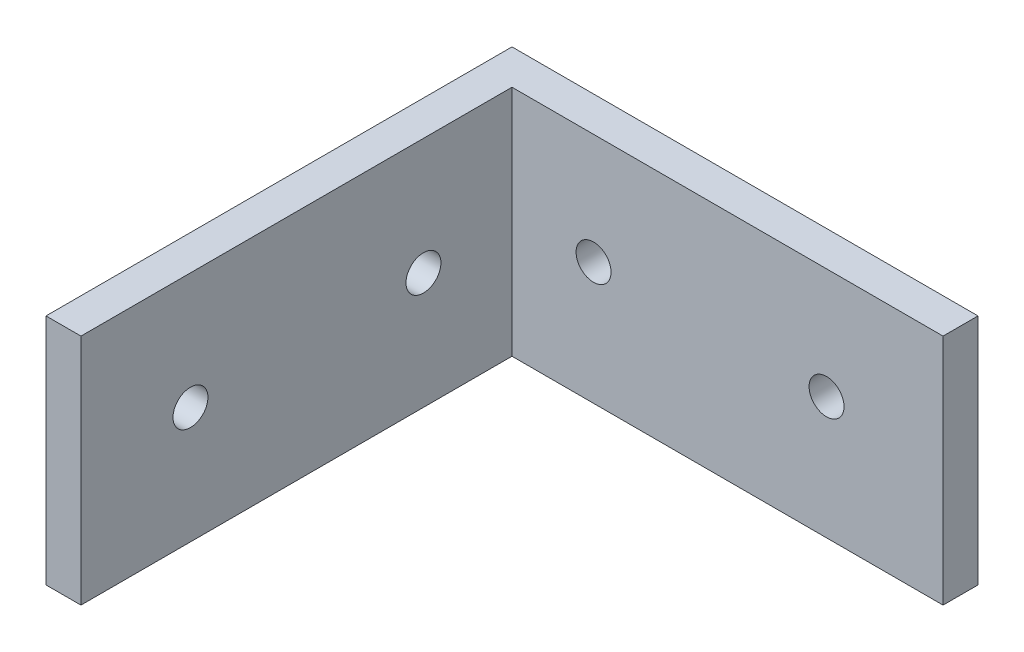
SolidWorks part; units mm, degrees
ref_plane "Plan de face" through (0, 0, 0) normal (0, 0, 1) x (1, 0, 0)
ref_plane "Plan de dessus" through (0, 0, 0) normal (0, 1, 0) x (1, 0, 0)
ref_plane "Plan de droite" through (0, 0, 0) normal (1, 0, 0) x (0, 0, -1)
sketch "Esquisse1" plane through (0, 0, 0) normal (0, 0, 1) x (1, 0, 0)
  line L1 (0, 0) -> (40, 0)
  line L2 (0, 0) -> (0, 20)
  line L3 (0, 20) -> (40, 20)
  line L4 (40, 0) -> (40, 20)
  dimension "D1" = 20
  dimension "D2" = 40
extrude "Boss.-Extru.1" add sketch "Esquisse1" along normal blind 3
sketch "Esquisse2" plane through (0, 0, 3) normal (0, 0, 1) x (1, 0, 0)
  line L0 (0, 20) -> (0, 0) construction
  line L1 (0, 0) -> (40, 0) construction
  circle A0 centre (10, 10.5) radius 1.5
  circle A1 centre (30, 10.5) radius 1.5
  dimension "D1" = 3
  dimension "D2" = 3
  dimension "D4" = 20
  dimension "D5" = 10.5
  dimension "D6" = 10.5
  dimension "D3" = 10
extrude "Enlèv. mat.-Extru.1" cut sketch "Esquisse2" against normal blind 3
sketch "Esquisse3" plane through (0, 0, 3) normal (0, 0, 1) x (1, 0, 0)
  line L0 (0, 0) -> (40, 0) construction
  line L1 (0, 20) -> (3, 20)
  line L2 (0, 20) -> (0, 0)
  line L3 (0, 0) -> (3, 0)
  line L4 (3, 20) -> (3, 0)
  dimension "D1" = 3
extrude "Boss.-Extru.2" add sketch "Esquisse3" along normal blind 37
sketch "Esquisse4" plane through (0, 0, 0) normal (-1, 0, 0) x (0, 0, 1)
  line L0 (0, 20) -> (0, 0) construction
  line L1 (40, 0) -> (0, 0) construction
  circle A0 centre (10.6, 10) radius 1.5
  circle A1 centre (30.6, 10) radius 1.5
  dimension "D1" = 3
  dimension "D2" = 3
  dimension "D3" = 20
  dimension "D4" = 10.6
  dimension "D5" = 10
  dimension "D6" = 10
extrude "Enlèv. mat.-Extru.2" cut sketch "Esquisse4" against normal blind 3
